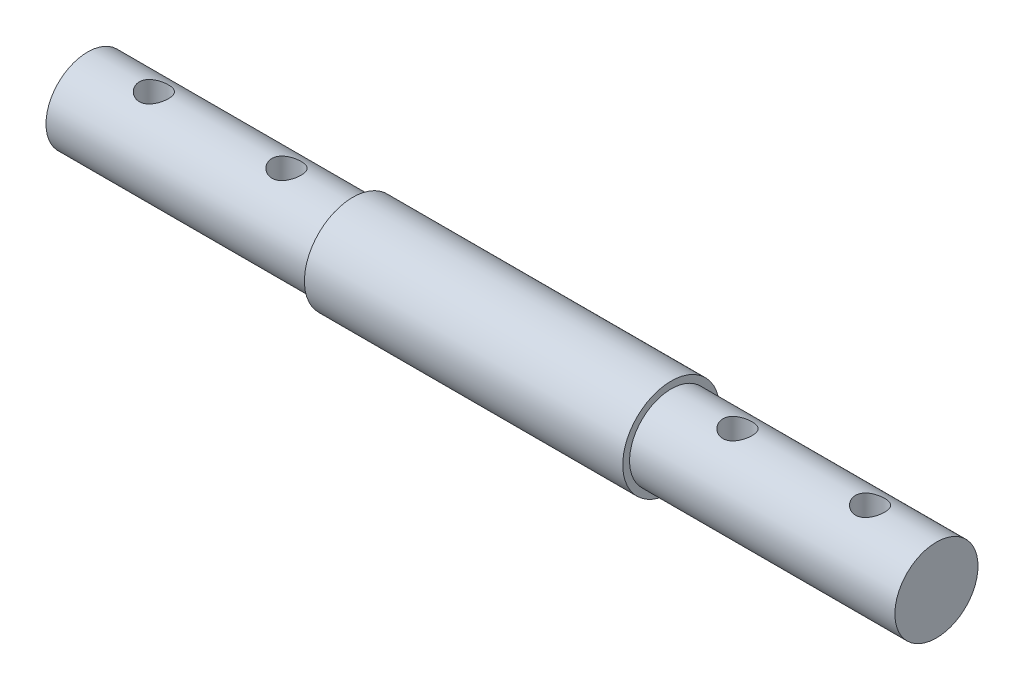
SolidWorks part; units mm, degrees
material "ASTM A36 Steel"
ref_plane "Front Plane" through (0, 0, 0) normal (0, 0, 1) x (1, 0, 0)
ref_plane "Top Plane" through (0, 0, 0) normal (0, 1, 0) x (1, 0, 0)
ref_plane "Right Plane" through (0, 0, 0) normal (1, 0, 0) x (0, 0, -1)
sketch "Sketch1" plane through (0, 0, 0) normal (1, 0, 0) x (0, 0, -1)
  circle A0 centre (0, 0) radius 36.5
  dimension "D1" = 73
extrude "Boss-Extrude1" add sketch "Sketch1" along normal blind 240
sketch "Sketch2" plane through (240, 0, 0) normal (1, 0, 0) x (0, 0, -1)
  circle A0 centre (0, 0) radius 31.34
  dimension "D1" = 62.68
extrude "Boss-Extrude2" add sketch "Sketch2" along normal blind 200
sketch "Sketch3" plane through (0, 0, 0) normal (-1, 0, 0) x (0, 0, 1)
  circle A0 centre (0, 0) radius 31.34
  dimension "D1" = 62.68
extrude "Boss-Extrude3" add sketch "Sketch3" along normal blind 200
sketch "Sketch4" plane through (0, 0, 0) normal (0, 1, 0) x (1, 0, 0)
  line L0 (0, 36.5) -> (0, -36.5) construction
  line L1 (240, -36.5) -> (240, 36.5) construction
  circle A0 centre (-50, 0) radius 11
  circle A1 centre (-150, 0) radius 11
  circle A2 centre (290, 0) radius 11
  circle A3 centre (390, 0) radius 11
  dimension "D1" = 22
  dimension "D2" = 22
  dimension "D3" = 50
  dimension "D4" = 100
  dimension "D5" = 22
  dimension "D6" = 22
  dimension "D7" = 50
  dimension "D8" = 100
extrude "Cut-Extrude1" cut sketch "Sketch4" against normal through all both and the other way through all
